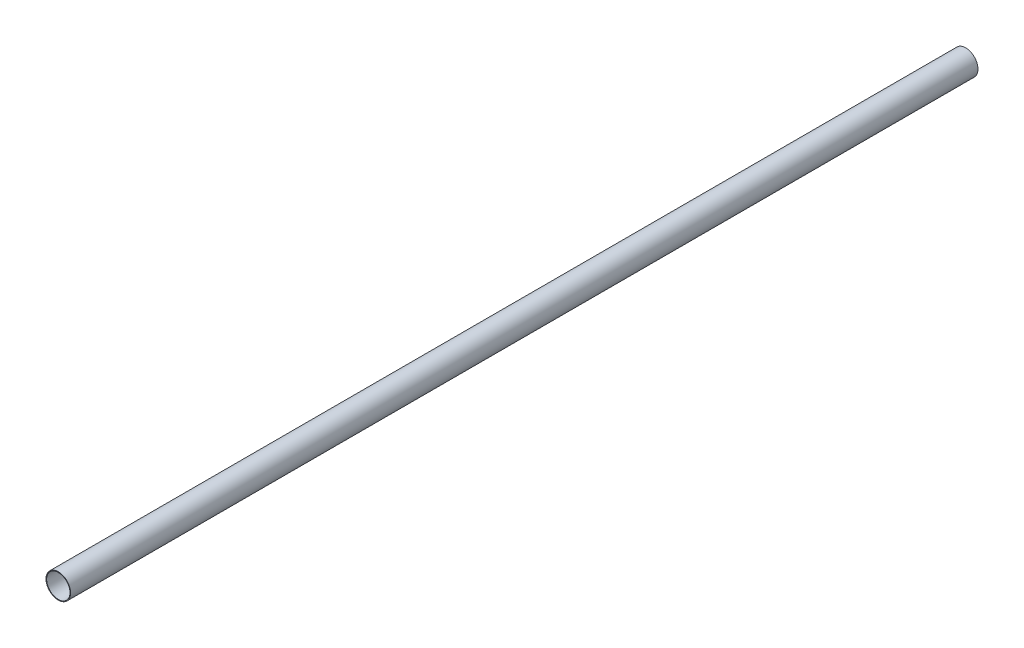
SolidWorks part; units mm, degrees
ref_plane "Front Plane" through (0, 0, 0) normal (0, 0, 1) x (1, 0, 0)
ref_plane "Top Plane" through (0, 0, 0) normal (0, 1, 0) x (1, 0, 0)
ref_plane "Right Plane" through (0, 0, 0) normal (1, 0, 0) x (0, 0, -1)
sketch "Sketch1" plane through (0, 0, 0) normal (0, 0, 1) x (1, 0, 0)
  circle A0 centre (0, 0) radius 11.25
  circle A1 centre (0, 0) radius 10.65
  dimension "D1" = 22.5
  dimension "D2" = 0.6
extrude "Boss-Extrude1" add sketch "Sketch1" along normal blind 829
